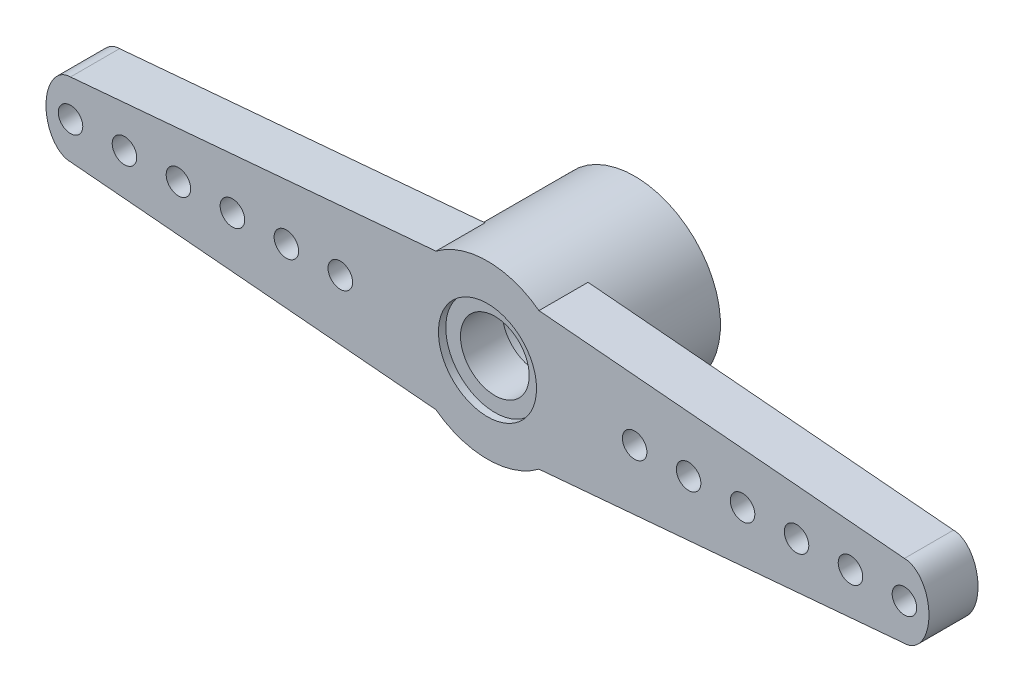
SolidWorks part; units mm, degrees
ref_plane "Alzado" through (0, 0, 0) normal (0, 0, 1) x (1, 0, 0)
ref_plane "Planta" through (0, 0, 0) normal (0, 1, 0) x (1, 0, 0)
ref_plane "Vista lateral" through (0, 0, 0) normal (1, 0, 0) x (0, 0, -1)
sketch "Croquis1" plane through (0, 0, 0) normal (0, 0, 1) x (1, 0, 0)
  line L0 (-18, 0) -> (18, 0) construction
  line L1 (0, -3.5) -> (0, 3.5) construction
  line L2 (-2.1, 2.8) -> (-2.1, -2.8) construction
  line L3 (2.1, 2.8) -> (2.1, -2.8) construction
  line L4 (-15.8, 0) -> (20.2, 0) construction
  line L5 (-13.6, 0) -> (22.4, 0) construction
  line L6 (-11.4, 0) -> (24.6, 0) construction
  line L7 (-9.2, 0) -> (26.8, 0) construction
  line L8 (-7, 0) -> (29, 0) construction
  line L9 (-17, -1.5) -> (-17, 1.5) construction
  line L10 (-2.1, 2.8) -> (-17, 1.5)
  line L11 (-2.1, -2.8) -> (-17, -1.5)
  line L12 (2.1, -2.8) -> (17, -1.5)
  line L13 (2.1, 2.8) -> (17, 1.5)
  arc A0 (-2.1, -2.8) -> (2.1, -2.8) centre (0, 0) ccw
  circle A1 centre (-17, 0) radius 0.5
  circle A2 centre (-14.8, 0) radius 0.5
  circle A3 centre (-12.6, 0) radius 0.5
  circle A4 centre (-10.4, 0) radius 0.5
  circle A5 centre (-8.2, 0) radius 0.5
  circle A6 centre (-6, 0) radius 0.5
  circle A7 centre (6, 0) radius 0.5
  circle A8 centre (8.2, 0) radius 0.5
  circle A9 centre (10.4, 0) radius 0.5
  circle A10 centre (12.6, 0) radius 0.5
  circle A11 centre (14.8, 0) radius 0.5
  circle A12 centre (17, 0) radius 0.5
  arc A13 (2.1, 2.8) -> (-2.1, 2.8) centre (0, 0) ccw
  ellipse E0 centre (-17, 0) end of major axis (-17, -1.5) minor radius 1 (-17, 1.5) -> (-17, -1.5) ccw
  ellipse E1 centre (17, 0) end of major axis (17, 1.5) minor radius 1 (17, 1.5) -> (17, -1.5) cw
  point P7 (0, 0)
  point P8 (0, 0)
  point P9 (0, 0)
  point P50 (-17, 0)
  dimension "D4" = 1
  dimension "D5" = 1
  dimension "D8" = 2.2
  dimension "D1" = 36
  dimension "D2" = 7
  dimension "D3" = 5.6
  dimension "D7" = 3
  dimension "D6" = 6
extrude "Saliente-Extruir1" add sketch "Croquis1" along normal blind 2
sketch "Croquis3" plane through (0, 0, 0) normal (0, 0, -1) x (-1, 0, 0)
  circle A0 centre (0, 0) radius 3.5
  circle A1 centre (0, 0) radius 2.25
  dimension "D1" = 7
  dimension "D2" = 4.5
extrude "Saliente-Extruir2" add sketch "Croquis3" along normal blind 4
sketch "Croquis4" plane through (0, 0, 0) normal (0, 0, -1) x (-1, 0, 0)
  circle A0 centre (0, 0) radius 1.4
  dimension "D1" = 2.8
extrude "Cortar-Extruir1" cut sketch "Croquis4" against normal through all contours A0
sketch "Croquis5" plane through (0, 0, 2) normal (0, 0, 1) x (1, 0, 0)
  circle A0 centre (0, 0) radius 2
  dimension "D1" = 4
extrude "Cortar-Extruir2" cut sketch "Croquis5" against normal blind 0.3
sketch "Croquis6" plane through (0, 0, -4) normal (0, 0, -1) x (-1, 0, 0)
  line L0 (0, 0) -> (0, -2.4) construction
  line L1 (0, -2.25) -> (0.1004, -2.3979)
  line L2 (0, -2.25) -> (-0.1004, -2.3979)
  line L3 (0.1004, -2.3979) -> (0.1674, -2.3942)
  line L4 (-0.1004, -2.3979) -> (-0.1674, -2.3942)
  line L5 (-0.4331, -2.3606) -> (-0.4988, -2.3476)
  line L6 (-0.313, -2.2281) -> (-0.4331, -2.3606)
  line L7 (-0.313, -2.2281) -> (-0.2342, -2.3885)
  line L8 (-0.2342, -2.3885) -> (-0.1674, -2.3942)
  line L9 (-0.7573, -2.2773) -> (-0.8206, -2.2553)
  line L10 (-0.62, -2.1629) -> (-0.7573, -2.2773)
  line L11 (-0.62, -2.1629) -> (-0.5642, -2.3327)
  line L12 (-0.5642, -2.3327) -> (-0.4988, -2.3476)
  line L13 (-1.0668, -2.1498) -> (-1.1264, -2.1192)
  line L14 (-0.9149, -2.0555) -> (-1.0668, -2.1498)
  line L15 (-0.9149, -2.0555) -> (-0.8833, -2.2315)
  line L16 (-0.8833, -2.2315) -> (-0.8206, -2.2553)
  line L17 (-1.3555, -1.9804) -> (-1.4103, -1.9418)
  line L18 (-1.192, -1.9082) -> (-1.3555, -1.9804)
  line L19 (-1.192, -1.9082) -> (-1.1852, -2.0869)
  line L20 (-1.1852, -2.0869) -> (-1.1264, -2.1192)
  line L21 (-1.6178, -1.7725) -> (-1.6667, -1.7266)
  line L22 (-1.4458, -1.7238) -> (-1.6178, -1.7725)
  line L23 (-1.4458, -1.7238) -> (-1.464, -1.9016)
  line L24 (-1.464, -1.9016) -> (-1.4103, -1.9418)
  line L25 (-1.8487, -1.5301) -> (-1.8907, -1.4778)
  line L26 (-1.6716, -1.5058) -> (-1.8487, -1.5301)
  line L27 (-1.6716, -1.5058) -> (-1.7143, -1.6794)
  line L28 (-1.7143, -1.6794) -> (-1.6667, -1.7266)
  line L29 (-2.0435, -1.2579) -> (-2.0779, -1.2003)
  line L30 (-1.8648, -1.2585) -> (-2.0435, -1.2579)
  line L31 (-1.8648, -1.2585) -> (-1.9312, -1.4245)
  line L32 (-1.9312, -1.4245) -> (-1.8907, -1.4778)
  line L33 (-2.1986, -0.9613) -> (-2.2246, -0.8995)
  line L34 (-2.0217, -0.9867) -> (-2.1986, -0.9613)
  line L35 (-2.0217, -0.9867) -> (-2.1106, -1.1418)
  line L36 (-2.1106, -1.1418) -> (-2.0779, -1.2003)
  line L37 (-2.3109, -0.6459) -> (-2.3281, -0.5811)
  line L38 (-2.1392, -0.6958) -> (-2.3109, -0.6459)
  line L39 (-2.1392, -0.6958) -> (-2.2489, -0.837)
  line L40 (-2.2489, -0.837) -> (-2.2246, -0.8995)
  line L41 (-2.3782, -0.318) -> (-2.3862, -0.2515)
  line L42 (-2.2152, -0.3913) -> (-2.3782, -0.318)
  line L43 (-2.2152, -0.3913) -> (-2.3434, -0.5159)
  line L44 (-2.3434, -0.5159) -> (-2.3281, -0.5811)
  line L45 (-2.3993, 0.016) -> (-2.3979, 0.0831)
  line L46 (-2.248, -0.0792) -> (-2.3993, 0.016)
  line L47 (-2.248, -0.0792) -> (-2.3923, -0.1847)
  line L48 (-2.3923, -0.1847) -> (-2.3862, -0.2515)
  line L49 (-2.3736, 0.3498) -> (-2.3629, 0.416)
  line L50 (-2.237, 0.2344) -> (-2.3736, 0.3498)
  line L51 (-2.237, 0.2344) -> (-2.3946, 0.15)
  line L52 (-2.3946, 0.15) -> (-2.3979, 0.0831)
  line L53 (-2.3017, 0.6767) -> (-2.2819, 0.7408)
  line L54 (-2.1825, 0.5435) -> (-2.3017, 0.6767)
  line L55 (-2.1825, 0.5435) -> (-2.3503, 0.4818)
  line L56 (-2.3503, 0.4818) -> (-2.3629, 0.416)
  line L57 (-2.185, 0.9905) -> (-2.1565, 1.0511)
  line L58 (-2.0855, 0.8419) -> (-2.185, 0.9905)
  line L59 (-2.0855, 0.8419) -> (-2.2603, 0.8042)
  line L60 (-2.2603, 0.8042) -> (-2.2819, 0.7408)
  line L61 (-2.0258, 1.2849) -> (-1.9891, 1.341)
  line L62 (-1.948, 1.124) -> (-2.0258, 1.2849)
  line L63 (-1.948, 1.124) -> (-2.1263, 1.111)
  line L64 (-2.1263, 1.111) -> (-2.1565, 1.0511)
  line L65 (-1.8272, 1.5543) -> (-1.783, 1.6048)
  line L66 (-1.7725, 1.3841) -> (-1.8272, 1.5543)
  line L67 (-1.7725, 1.3841) -> (-1.9509, 1.3961)
  line L68 (-1.9509, 1.3961) -> (-1.9891, 1.341)
  line L69 (-1.593, 1.7935) -> (-1.5423, 1.8373)
  line L70 (-1.5625, 1.6173) -> (-1.593, 1.7935)
  line L71 (-1.5625, 1.6173) -> (-1.7375, 1.654)
  line L72 (-1.7375, 1.654) -> (-1.783, 1.6048)
  line L73 (-1.3278, 1.9978) -> (-1.2714, 2.0341)
  line L74 (-1.3221, 1.8191) -> (-1.3278, 1.9978)
  line L75 (-1.3221, 1.8191) -> (-1.4903, 1.8797)
  line L76 (-1.4903, 1.8797) -> (-1.5423, 1.8373)
  line L77 (-1.0367, 2.1631) -> (-0.9759, 2.1912)
  line L78 (-1.056, 1.9854) -> (-1.0367, 2.1631)
  line L79 (-1.056, 1.9854) -> (-1.2141, 2.0688)
  line L80 (-1.2141, 2.0688) -> (-1.2714, 2.0341)
  line L81 (-0.7255, 2.2863) -> (-0.6613, 2.3057)
  line L82 (-0.7693, 2.113) -> (-0.7255, 2.2863)
  line L83 (-0.7693, 2.113) -> (-0.9143, 2.2176)
  line L84 (-0.9143, 2.2176) -> (-0.9759, 2.1912)
  line L85 (-0.4002, 2.365) -> (-0.3339, 2.3753)
  line L86 (-0.4677, 2.1995) -> (-0.4002, 2.365)
  line L87 (-0.4677, 2.1995) -> (-0.5967, 2.3233)
  line L88 (-0.5967, 2.3233) -> (-0.6613, 2.3057)
  line L89 (-0.067, 2.3977) -> (0, 2.3986)
  line L90 (-0.1569, 2.2432) -> (-0.067, 2.3977)
  line L91 (-0.1569, 2.2432) -> (-0.2674, 2.3837)
  line L92 (-0.2674, 2.3837) -> (-0.3339, 2.3753)
  line L93 (0.2674, 2.3837) -> (0.3339, 2.3753)
  line L94 (0.1569, 2.2432) -> (0.2674, 2.3837)
  line L95 (0.1569, 2.2432) -> (0.067, 2.3977)
  line L96 (0.067, 2.3977) -> (0, 2.3986)
  line L97 (0.5967, 2.3233) -> (0.6613, 2.3057)
  line L98 (0.4677, 2.1995) -> (0.5967, 2.3233)
  line L99 (0.4677, 2.1995) -> (0.4002, 2.365)
  line L100 (0.4002, 2.365) -> (0.3339, 2.3753)
  line L101 (0.9143, 2.2176) -> (0.9759, 2.1912)
  line L102 (0.7693, 2.113) -> (0.9143, 2.2176)
  line L103 (0.7693, 2.113) -> (0.7255, 2.2863)
  line L104 (0.7255, 2.2863) -> (0.6613, 2.3057)
  line L105 (1.2141, 2.0688) -> (1.2714, 2.0341)
  line L106 (1.056, 1.9854) -> (1.2141, 2.0688)
  line L107 (1.056, 1.9854) -> (1.0367, 2.1631)
  line L108 (1.0367, 2.1631) -> (0.9759, 2.1912)
  line L109 (1.4903, 1.8797) -> (1.5423, 1.8373)
  line L110 (1.3221, 1.8191) -> (1.4903, 1.8797)
  line L111 (1.3221, 1.8191) -> (1.3278, 1.9978)
  line L112 (1.3278, 1.9978) -> (1.2714, 2.0341)
  line L113 (1.7375, 1.654) -> (1.783, 1.6048)
  line L114 (1.5625, 1.6173) -> (1.7375, 1.654)
  line L115 (1.5625, 1.6173) -> (1.593, 1.7935)
  line L116 (1.593, 1.7935) -> (1.5423, 1.8373)
  line L117 (1.9509, 1.3961) -> (1.9891, 1.341)
  line L118 (1.7725, 1.3841) -> (1.9509, 1.3961)
  line L119 (1.7725, 1.3841) -> (1.8272, 1.5543)
  line L120 (1.8272, 1.5543) -> (1.783, 1.6048)
  line L121 (2.1263, 1.111) -> (2.1565, 1.0511)
  line L122 (1.948, 1.124) -> (2.1263, 1.111)
  line L123 (1.948, 1.124) -> (2.0258, 1.2849)
  line L124 (2.0258, 1.2849) -> (1.9891, 1.341)
  line L125 (2.2603, 0.8042) -> (2.2819, 0.7408)
  line L126 (2.0855, 0.8419) -> (2.2603, 0.8042)
  line L127 (2.0855, 0.8419) -> (2.185, 0.9905)
  line L128 (2.185, 0.9905) -> (2.1565, 1.0511)
  line L129 (2.3503, 0.4818) -> (2.3629, 0.416)
  line L130 (2.1825, 0.5435) -> (2.3503, 0.4818)
  line L131 (2.1825, 0.5435) -> (2.3017, 0.6767)
  line L132 (2.3017, 0.6767) -> (2.2819, 0.7408)
  line L133 (2.3946, 0.15) -> (2.3979, 0.0831)
  line L134 (2.237, 0.2344) -> (2.3946, 0.15)
  line L135 (2.237, 0.2344) -> (2.3736, 0.3498)
  line L136 (2.3736, 0.3498) -> (2.3629, 0.416)
  line L137 (2.3923, -0.1847) -> (2.3862, -0.2515)
  line L138 (2.248, -0.0792) -> (2.3923, -0.1847)
  line L139 (2.248, -0.0792) -> (2.3993, 0.016)
  line L140 (2.3993, 0.016) -> (2.3979, 0.0831)
  line L141 (2.3434, -0.5159) -> (2.3281, -0.5811)
  line L142 (2.2152, -0.3913) -> (2.3434, -0.5159)
  line L143 (2.2152, -0.3913) -> (2.3782, -0.318)
  line L144 (2.3782, -0.318) -> (2.3862, -0.2515)
  line L145 (2.2489, -0.837) -> (2.2246, -0.8995)
  line L146 (2.1392, -0.6958) -> (2.2489, -0.837)
  line L147 (2.1392, -0.6958) -> (2.3109, -0.6459)
  line L148 (2.3109, -0.6459) -> (2.3281, -0.5811)
  line L149 (2.1106, -1.1418) -> (2.0779, -1.2003)
  line L150 (2.0217, -0.9867) -> (2.1106, -1.1418)
  line L151 (2.0217, -0.9867) -> (2.1986, -0.9613)
  line L152 (2.1986, -0.9613) -> (2.2246, -0.8995)
  line L153 (1.9312, -1.4245) -> (1.8907, -1.4778)
  line L154 (1.8648, -1.2585) -> (1.9312, -1.4245)
  line L155 (1.8648, -1.2585) -> (2.0435, -1.2579)
  line L156 (2.0435, -1.2579) -> (2.0779, -1.2003)
  line L157 (1.7143, -1.6794) -> (1.6667, -1.7266)
  line L158 (1.6716, -1.5058) -> (1.7143, -1.6794)
  line L159 (1.6716, -1.5058) -> (1.8487, -1.5301)
  line L160 (1.8487, -1.5301) -> (1.8907, -1.4778)
  line L161 (1.464, -1.9016) -> (1.4103, -1.9418)
  line L162 (1.4458, -1.7238) -> (1.464, -1.9016)
  line L163 (1.4458, -1.7238) -> (1.6178, -1.7725)
  line L164 (1.6178, -1.7725) -> (1.6667, -1.7266)
  line L165 (1.1852, -2.0869) -> (1.1264, -2.1192)
  line L166 (1.192, -1.9082) -> (1.1852, -2.0869)
  line L167 (1.192, -1.9082) -> (1.3555, -1.9804)
  line L168 (1.3555, -1.9804) -> (1.4103, -1.9418)
  line L169 (0.8833, -2.2315) -> (0.8206, -2.2553)
  line L170 (0.9149, -2.0555) -> (0.8833, -2.2315)
  line L171 (0.9149, -2.0555) -> (1.0668, -2.1498)
  line L172 (1.0668, -2.1498) -> (1.1264, -2.1192)
  line L173 (0.5642, -2.3327) -> (0.4988, -2.3476)
  line L174 (0.62, -2.1629) -> (0.5642, -2.3327)
  line L175 (0.62, -2.1629) -> (0.7573, -2.2773)
  line L176 (0.7573, -2.2773) -> (0.8206, -2.2553)
  line L177 (0.2342, -2.3885) -> (0.1674, -2.3942)
  line L178 (0.313, -2.2281) -> (0.2342, -2.3885)
  line L179 (0.313, -2.2281) -> (0.4331, -2.3606)
  line L180 (0.4331, -2.3606) -> (0.4988, -2.3476)
  circle A0 centre (0, 0) radius 2.25 construction
  circle A1 centre (0, 0) radius 2.25 construction
  circle A2 centre (0, 0) radius 2.4 construction
  point P233 (0, -0.0007)
  dimension "D1" = 0.15
  dimension "D2" = 45
extrude "Cortar-Extruir4" cut sketch "Croquis6" against normal blind 2
